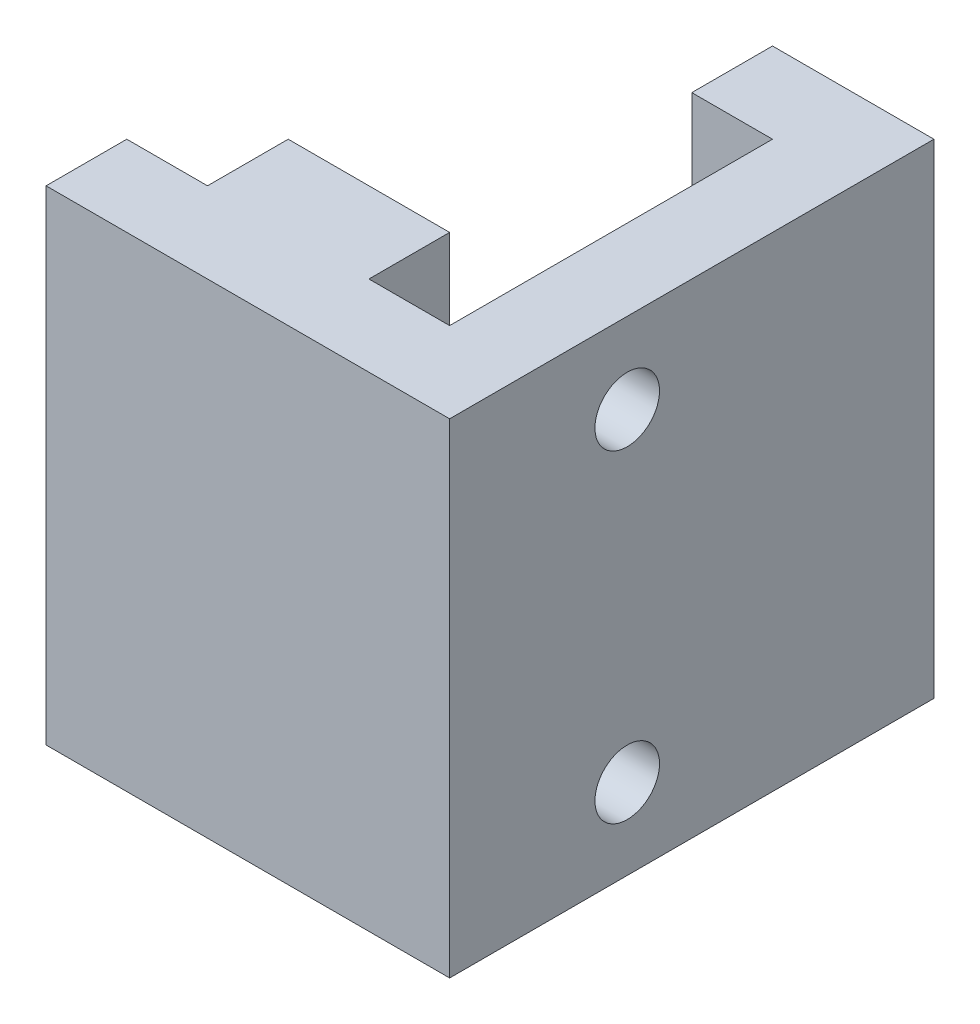
SolidWorks part; units mm, degrees
ref_plane "Front Plane" through (0, 0, 0) normal (0, 0, 1) x (1, 0, 0)
ref_plane "Top Plane" through (0, 0, 0) normal (0, 1, 0) x (1, 0, 0)
ref_plane "Right Plane" through (0, 0, 0) normal (1, 0, 0) x (0, 0, -1)
sketch "Sketch1" plane through (0, 0, 0) normal (0, 1, 0) x (1, 0, 0)
  line L0 (0, 5) -> (0, 0)
  line L1 (0, 0) -> (25, 0)
  line L2 (25, 0) -> (25, 30)
  line L3 (25, 30) -> (15, 30)
  line L4 (15, 30) -> (15, 25)
  line L5 (15, 25) -> (20, 25)
  line L6 (20, 25) -> (20, 5)
  line L7 (20, 5) -> (15, 5)
  line L8 (15, 5) -> (15, 10)
  line L9 (15, 10) -> (5, 10)
  line L10 (5, 10) -> (5, 5)
  line L11 (5, 5) -> (0, 5)
  dimension "D1" = 5
  dimension "D2" = 10
  dimension "D3" = 5
  dimension "D4" = 20
  dimension "D5" = 5
  dimension "D6" = 5
  dimension "D7" = 10
  dimension "D8" = 5
extrude "Boss-Extrude1" add sketch "Sketch1" along normal blind 30
sketch "Sketch2" plane through (25, 0, 0) normal (1, 0, 0) x (0, 0, -1)
  line L0 (0, 30) -> (30, 30) construction
  line L1 (0, 30) -> (0, 0) construction
  circle A0 centre (11, 25) radius 2
  circle A1 centre (11, 5) radius 2
  point P8 (7.0068, 5.4027)
  point P9 (0, 0)
  dimension "D1" = 5
  dimension "D3" = 4
  dimension "D4" = 4
  dimension "D2" = 20
  dimension "D5" = 11
extrude "Cut-Extrude1" cut sketch "Sketch2" against normal blind 3
